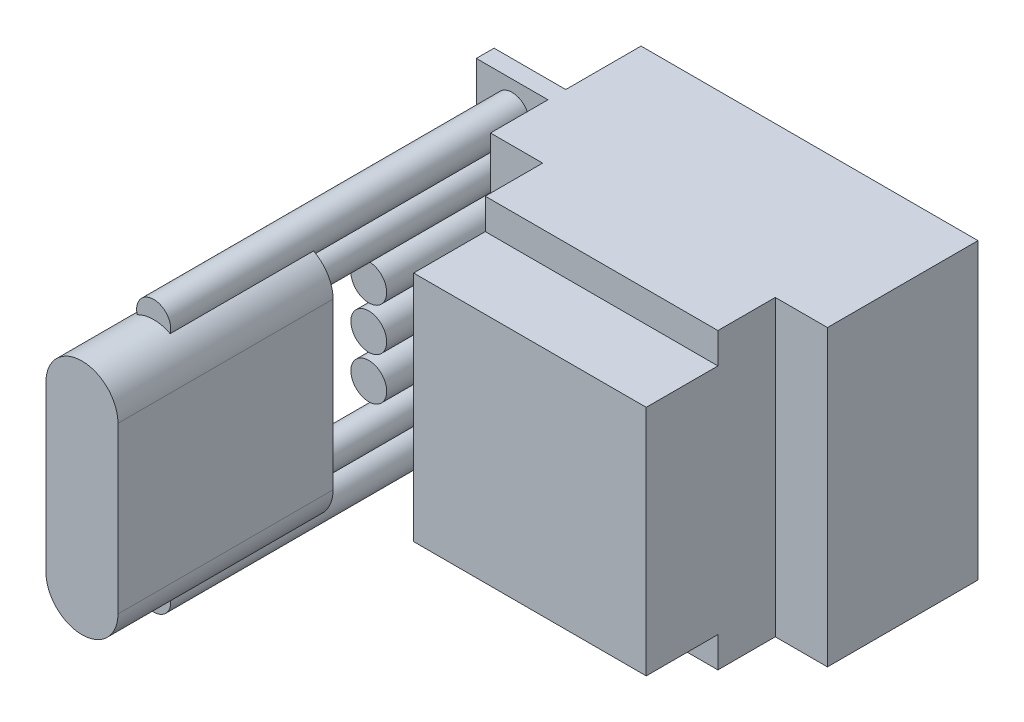
SolidWorks part; units mm, degrees
ref_plane "Спереди" through (0, 0, 0) normal (0, 0, 1) x (1, 0, 0)
ref_plane "Сверху" through (0, 0, 0) normal (0, 1, 0) x (1, 0, 0)
ref_plane "Справа" through (0, 0, 0) normal (1, 0, 0) x (0, 0, -1)
sketch "Эскиз1" plane through (0, 0, 0) normal (0, 0, 1) x (1, 0, 0)
  line L1 (-23.5, 20.5) -> (23.5, 20.5)
  line L2 (-23.5, 20.5) -> (-23.5, -20.5)
  line L3 (-23.5, -20.5) -> (23.5, -20.5)
  line L4 (23.5, 20.5) -> (23.5, -20.5)
  line L5 (-23.5, 20.5) -> (23.5, -20.5) construction
  line L6 (-23.5, -20.5) -> (23.5, 20.5) construction
  point P0 (0, 0)
  dimension "D1" = 47
  dimension "D2" = 41
extrude "Бобышка-Вытянуть1" add sketch "Эскиз1" along normal blind 29
sketch "Эскиз2" plane through (0, 0, 29) normal (0, 0, 1) x (1, 0, 0)
  line L0 (-23.5, -20.5) -> (23.5, -20.5) construction
  line L1 (-23.5, 20.5) -> (-16.2243, 20.5)
  line L2 (-23.5, 20.5) -> (-23.5, -20.5)
  line L3 (-23.5, -20.5) -> (-16.2243, -20.5)
  line L4 (-16.2243, 20.5) -> (-16.2243, -20.5)
  line L5 (0, 8.0306) -> (0, -6.4001) construction
  line L6 (16.2243, 20.5) -> (16.2243, -20.5)
  line L7 (23.5, -20.5) -> (16.2243, -20.5)
  line L8 (23.5, 20.5) -> (23.5, -20.5)
  line L9 (23.5, 20.5) -> (16.2243, 20.5)
extrude "Вырез-Вытянуть1" cut sketch "Эскиз2" against normal blind 8
sketch "Эскиз3" plane through (0, 0, 29) normal (0, 0, 1) x (1, 0, 0)
  line L0 (16.2243, 20.5) -> (16.2243, -20.5) construction
  line L1 (-16.2243, 16.2243) -> (16.2243, 16.2243)
  line L2 (-16.2243, 16.2243) -> (-16.2243, -16.2243)
  line L3 (-16.2243, -16.2243) -> (16.2243, -16.2243)
  line L4 (16.2243, 16.2243) -> (16.2243, -16.2243)
  line L5 (-16.2243, 16.2243) -> (16.2243, -16.2243) construction
  line L6 (-16.2243, -16.2243) -> (16.2243, 16.2243) construction
  point P0 (0, 0)
extrude "Бобышка-Вытянуть2" add sketch "Эскиз3" along normal blind 10
sketch "Эскиз4" plane through (-23.5, 0, 0) normal (-1, 0, 0) x (0, 0, 1)
  line L0 (21, 20.5) -> (0, 20.5) construction
  line L1 (10.5, 20.5) -> (12.9777, 20.5)
  line L2 (10.5, 20.5) -> (10.5, -20.5)
  line L3 (10.5, -20.5) -> (12.9777, -20.5)
  line L4 (12.9777, 20.5) -> (12.9777, -20.5)
  line L5 (21, -20.5) -> (0, -20.5) construction
extrude "Бобышка-Вытянуть3" add sketch "Эскиз4" along normal blind 10
sketch "Эскиз5" plane through (0, 0, 12.9777) normal (0, 0, 1) x (1, 0, 0)
  line L0 (-28.5, 20.5) -> (-28.5, -20.5) construction
  line L1 (-33.5, 20.5) -> (-23.5, 20.5) construction
  line L2 (-33.5, -20.5) -> (-23.5, -20.5) construction
  line L3 (-33.5, 0) -> (-24.5315, 0) construction
  line L4 (-33.5, -20.5) -> (-33.5, 20.5) construction
  circle A0 centre (-28.5, 16.5098) radius 2.3815
  circle A1 centre (-28.5, -16.5098) radius 2.3815
extrude "Бобышка-Вытянуть4" add sketch "Эскиз5" along normal blind 50
sketch "Эскиз6" plane through (0, 0, 12.9777) normal (0, 0, 1) x (1, 0, 0)
  line L0 (-28.5, 20.5) -> (-28.5, -20.5) construction
  line L1 (-33.5, 20.5) -> (-23.5, 20.5) construction
  line L2 (-33.5, -20.5) -> (-23.5, -20.5) construction
  circle A0 centre (-28.5, 5.9698) radius 2.5
  circle A1 centre (-28.5, 0) radius 2.5
  circle A2 centre (-28.5, -5.9771) radius 2.5
  dimension "D1" = 5
  dimension "D2" = 5
  dimension "D3" = 5
extrude "Бобышка-Вытянуть5" add sketch "Эскиз6" along normal blind 20
sketch "Эскиз7" plane through (0, 0, 12.9777) normal (0, 0, 1) x (1, 0, 0)
  line L0 (-28.5, 20.5) -> (-28.5, -20.5) construction
  line L1 (-33.5, 20.5) -> (-23.5, 20.5) construction
  line L2 (-33.5, -20.5) -> (-23.5, -20.5) construction
  circle A0 centre (-28.5, 11.4299) radius 2.2187
  circle A1 centre (-28.5, -11.6051) radius 2.107
extrude "Бобышка-Вытянуть6" add sketch "Эскиз7" along normal blind 30
sketch "Эскиз8" plane through (0, 0, 42.9777) normal (0, 0, 1) x (1, 0, 0)
  line L0 (-28.5, 11.4299) -> (-28.5, -11.6051) construction
  line L1 (-23.4805, 11.4299) -> (-23.4805, -11.6051)
  line L2 (-33.5195, 11.4299) -> (-33.5195, -11.6051)
  arc A0 (-23.4805, 11.4299) -> (-33.5195, 11.4299) centre (-28.5, 11.4299) ccw
  arc A1 (-33.5195, -11.6051) -> (-23.4805, -11.6051) centre (-28.5, -11.6051) ccw
  point P4 (-28.5, -0.0876)
extrude "Бобышка-Вытянуть7" add sketch "Эскиз8" along normal blind 30
